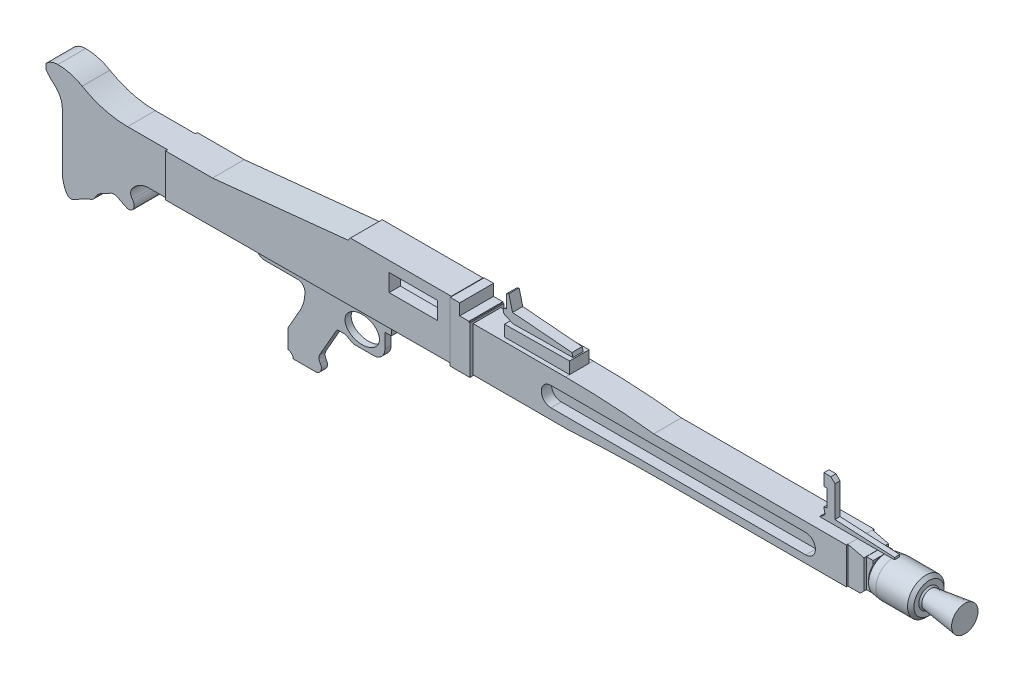
SolidWorks part; units mm, degrees
ref_plane "Front Plane" through (0, 0, 0) normal (0, 0, 1) x (1, 0, 0)
ref_plane "Top Plane" through (0, 0, 0) normal (0, 1, 0) x (1, 0, 0)
ref_plane "Right Plane" through (0, 0, 0) normal (1, 0, 0) x (0, 0, -1)
sketch "Sketch2" plane through (0, 0, 0) normal (0, 0, 1) x (1, 0, 0)
  line L0 (14.7008, 153.5347) -> (898.7815, 153.5347) construction
  dimension "D1" = 884.0807
sketch "Sketch3" plane through (0, 0, 0) normal (0, 0, 1) x (1, 0, 0)
  line L0 (133.1499, 139.8957) -> (133.1499, 98.4718)
  line L1 (133.1499, 98.4718) -> (411.7498, 99.671)
  line L2 (411.7498, 99.671) -> (411.7498, 156.4491)
  line L3 (411.7498, 156.4491) -> (313.434, 156.4491)
  line L4 (313.434, 156.4491) -> (311.325, 153.5347)
  line L5 (14.7008, 153.5347) -> (898.7815, 153.5347) construction
  line L6 (311.325, 153.5347) -> (179.0076, 139.8957)
  line L7 (179.0076, 139.8957) -> (133.1499, 139.8957)
extrude "Boss-Extrude1" add sketch "Sketch3" along normal mid plane 31
sketch "Sketch4" plane through (0, 0, 0) normal (0, 0, 1) x (1, 0, 0)
  line L0 (411.7498, 156.033) -> (420.9758, 156.033)
  line L1 (411.7498, 99.671) -> (411.7498, 156.4491) construction
  line L2 (420.9758, 156.033) -> (420.9758, 144.9785)
  line L3 (420.9758, 144.9785) -> (430.0091, 144.9785)
  line L4 (430.0091, 144.9785) -> (430.0091, 143.9886)
  line L5 (430.0091, 143.9886) -> (431.0197, 143.9886)
  line L6 (431.0197, 143.9886) -> (431.0197, 141.9943)
  line L7 (431.0197, 141.9943) -> (431.0197, 97.9537)
  line L8 (431.0197, 97.9537) -> (411.7498, 97.9537)
  line L9 (411.7498, 97.9537) -> (411.7498, 99.671)
  line L10 (411.7498, 99.671) -> (411.7498, 156.033)
extrude "Boss-Extrude2" add sketch "Sketch4" along normal mid plane 33
sketch "Sketch5" plane through (0, 0, 0) normal (0, 0, 1) x (1, 0, 0)
  line L0 (133.1499, 139.8957) -> (94.2529, 139.8957)
  line L1 (133.1499, 139.8957) -> (133.1499, 98.4718)
  line L2 (133.1499, 98.4718) -> (115.1309, 98.4718)
  line L3 (30.6087, 69.3461) -> (30.6087, 122.8292)
  line L4 (14.7008, 148.4374) -> (14.7008, 153.5347)
  arc A0 (94.2529, 139.8957) -> (49.9783, 151.9188) centre (94.2529, 227.4269) cw
  arc A1 (49.9783, 151.9188) -> (26.2526, 158.3616) centre (26.2526, 111.4559) ccw
  arc A2 (26.2526, 158.3616) -> (14.7008, 153.5347) centre (26.2526, 142.1251) ccw
  arc A3 (115.1309, 98.4718) -> (98.2336, 89.0087) centre (115.1309, 78.6544) ccw
  arc A4 (98.2336, 89.0087) -> (98.8895, 80.7837) centre (104.2099, 85.3466) ccw
  arc A5 (98.8895, 80.7837) -> (100.0051, 73.4816) centre (93.5886, 76.2376) cw
  arc A6 (100.0051, 73.4816) -> (93.5886, 70.9209) centre (95.5165, 75.4095) cw
  arc A7 (93.5886, 70.9209) -> (84.488, 75.4095) centre (131.7264, 159.714) cw
  arc A8 (84.488, 75.4095) -> (77.693, 75.4095) centre (81.0905, 69.3461) ccw
  arc A9 (77.693, 75.4095) -> (69.1582, 70.8723) centre (-29.0893, 265.9797) cw
  arc A10 (69.1582, 70.8723) -> (62.7211, 64.3963) centre (75.6482, 57.9841) ccw
  arc A11 (62.7211, 64.3963) -> (59.2285, 61.0407) centre (56.3051, 67.5788) cw
  arc A12 (59.2285, 61.0407) -> (41.7659, 52.0012) centre (129.4371, -95.9766) ccw
  arc A13 (41.7659, 52.0012) -> (34.8781, 53.7639) centre (39.2033, 56.3264) cw
  arc A14 (34.8781, 53.7639) -> (30.6087, 69.3461) centre (61.1788, 69.3461) cw
  arc A15 (30.6087, 122.8292) -> (22.4442, 139.8957) centre (8.6893, 122.8292) ccw
  arc A16 (22.4442, 139.8957) -> (14.7008, 148.4374) centre (45.7254, 168.7818) cw
extrude "Boss-Extrude3" add sketch "Sketch5" along normal mid plane 27
sketch "Sketch6" plane through (0, 0, 0) normal (0, 0, 1) x (1, 0, 0)
  line L0 (431.0197, 141.9851) -> (521.1439, 141.9851)
  line L1 (431.0197, 97.9537) -> (431.0197, 143.9886) construction
  line L2 (607.1546, 136.9962) -> (794.9048, 136.9962)
  line L3 (794.9048, 136.9962) -> (794.9048, 101.6278)
  line L4 (794.9048, 101.6278) -> (617.7858, 101.6278)
  line L5 (523.6562, 98.7043) -> (431.0197, 98.7043)
  line L6 (431.0197, 98.7043) -> (431.0197, 141.9851)
  arc A0 (521.1439, 141.9851) -> (607.1546, 136.9962) centre (521.1439, -601.9324) cw
  arc A1 (617.7858, 101.6278) -> (523.6562, 98.7043) centre (617.7858, -1415.198) ccw
extrude "Boss-Extrude4" add sketch "Sketch6" along normal mid plane 27
sketch "Sketch7" plane through (0, 0, 0) normal (0, 0, 1) x (1, 0, 0)
  line L0 (794.9048, 136.9962) -> (810.5012, 133.2202)
  line L1 (810.5012, 133.2202) -> (810.5012, 105.1026)
  line L2 (810.5012, 105.1026) -> (807.0264, 101.6278)
  line L3 (807.0264, 101.6278) -> (794.9048, 101.6278)
  line L4 (794.9048, 136.9962) -> (794.9048, 101.6278)
extrude "Boss-Extrude5" add sketch "Sketch7" along normal mid plane 24
sketch "Sketch8" plane through (0, 0, 0) normal (0, 0, 1) x (1, 0, 0)
  line L0 (810.5012, 132.9965) -> (816.9976, 132.9965)
  line L1 (810.5012, 105.1026) -> (810.5012, 133.2202) construction
  line L2 (816.9976, 132.9965) -> (816.9976, 105.1026)
  line L3 (816.9976, 105.1026) -> (810.5012, 105.1026)
  line L4 (810.5012, 105.1026) -> (810.5012, 132.9965)
extrude "Boss-Extrude6" add sketch "Sketch8" along normal mid plane 19
sketch "Sketch9" plane through (0, 0, 0) normal (0, 0, 1) x (1, 0, 0)
  line L0 (457.5847, 141.9851) -> (457.5847, 152.7766)
  line L1 (521.1439, 141.9851) -> (431.0197, 141.9851) construction
  line L2 (457.5847, 152.7766) -> (521.1439, 153.5347)
  line L3 (14.7008, 153.5347) -> (898.7815, 153.5347) construction
  line L4 (521.1439, 153.5347) -> (521.1439, 141.9851)
  line L5 (521.1439, 141.9851) -> (457.5847, 141.9851)
extrude "Boss-Extrude7" add sketch "Sketch9" along normal mid plane 19
sketch "Sketch10" plane through (0, 0, 0) normal (0, 0, 1) x (1, 0, 0)
  line L0 (519.8698, 153.5347) -> (518.9166, 157.2999)
  line L1 (14.7008, 153.5347) -> (898.7815, 153.5347) construction
  line L2 (518.9166, 157.2999) -> (460.9658, 162.1609)
  line L3 (460.9658, 162.1609) -> (457.4142, 176.1911)
  line L4 (457.4142, 176.1911) -> (455.0466, 174.9369)
  line L5 (455.0466, 174.9369) -> (455.0466, 162.1609)
  line L6 (455.0466, 155.9393) -> (460.9658, 152.8169)
  line L7 (521.1439, 153.5347) -> (457.5847, 152.7766) construction
  line L8 (460.9658, 152.8169) -> (519.8698, 153.5347)
  arc A0 (455.0466, 162.1609) -> (451.9358, 159.0501) centre (455.0466, 159.0501) ccw
  arc A1 (451.9358, 159.0501) -> (455.0466, 155.9393) centre (455.0466, 159.0501) ccw
extrude "Boss-Extrude8" add sketch "Sketch10" along normal mid plane 10 separate body
sketch "Sketch11" plane through (0, 0, 0) normal (0, 0, 1) x (1, 0, 0)
  line L0 (757.7007, 136.9962) -> (763.235, 141.021)
  line L1 (794.9048, 136.9962) -> (607.1546, 136.9962) construction
  line L2 (763.235, 141.021) -> (761.9898, 147.247)
  line L3 (761.9898, 147.247) -> (765.2092, 147.8909)
  line L4 (765.2092, 147.8909) -> (765.2092, 164.68)
  line L5 (765.2092, 164.68) -> (761.9898, 164.68)
  line L6 (761.9898, 164.68) -> (761.9898, 176.1636)
  line L7 (761.9898, 176.1636) -> (768.7693, 176.1636)
  line L8 (768.7693, 176.1636) -> (772.7816, 172.1512)
  line L9 (772.7816, 172.1512) -> (772.7816, 141.9895)
  line L10 (772.7816, 141.9895) -> (830.8844, 139.0086)
  line L11 (830.8844, 139.0086) -> (830.8844, 136.9962)
  line L12 (830.8844, 136.9962) -> (757.7007, 136.9962)
extrude "Boss-Extrude9" add sketch "Sketch11" along normal mid plane 5
sketch "Sketch12" plane through (0, 0, 0) normal (0, 0, 1) x (1, 0, 0)
  line L0 (208.8422, 98.7976) -> (208.8422, 92.0083)
  line L1 (133.1499, 98.4718) -> (411.7498, 99.671) construction
  line L2 (217.4889, 83.3616) -> (249.4184, 83.3616)
  line L3 (251.8692, 58.3778) -> (240.0102, 37.6418)
  line L4 (240.0102, 37.6418) -> (240.0102, 19.2458)
  line L5 (245.1891, 14.0669) -> (266.8401, 14.0669)
  line L6 (271.0539, 30.6103) -> (287.2395, 58.9114)
  line L7 (289.4063, 60.1684) -> (295.9274, 60.1684)
  line L8 (295.9274, 60.1684) -> (303.9879, 55.9915)
  line L9 (303.9879, 55.9915) -> (323.5844, 55.9915)
  line L10 (334.5626, 66.9698) -> (334.5626, 81.2581)
  line L11 (334.5626, 81.2581) -> (340.8552, 81.2581)
  line L12 (340.8552, 81.2581) -> (340.8552, 99.3658)
  line L13 (340.8552, 99.3658) -> (208.8422, 98.7976)
  arc A0 (208.8422, 92.0083) -> (217.4889, 83.3616) centre (217.4889, 92.0083) ccw
  arc A1 (249.4184, 83.3616) -> (256.6002, 76.1798) centre (249.4184, 76.1798) cw
  arc A2 (256.6002, 76.1798) -> (251.8692, 58.3778) centre (220.7417, 76.1798) cw
  arc A3 (240.0102, 19.2458) -> (245.1891, 14.0669) centre (240.0102, 14.0669) cw
  arc A4 (266.8401, 14.0669) -> (271.6285, 23.2042) centre (266.8401, 19.8902) ccw
  arc A5 (271.6285, 23.2042) -> (271.0539, 30.6103) centre (277.6908, 27.3999) cw
  arc A6 (287.2395, 58.9114) -> (289.4063, 60.1684) centre (289.4063, 57.6722) cw
  arc A7 (323.5844, 55.9915) -> (334.5626, 66.9698) centre (323.5844, 66.9698) ccw
  ellipse E0 centre (312.4473, 72.4103) end of major axis (329.2097, 72.4103) minor radius 12.7891
extrude "Boss-Extrude10" add sketch "Sketch12" along normal mid plane 6
sketch "Sketch13" plane through (0, 0, 0) normal (0, 0, 1) x (1, 0, 0)
  line L0 (816.9976, 119.0496) -> (904.5437, 119.0496) construction
  line L1 (816.9976, 105.1026) -> (816.9976, 132.9965) construction
  line L11 (816.9976, 119.0496) -> (816.9976, 132.9965)
  line L14 (816.9976, 132.9965) -> (819.7407, 135.7396)
  line L15 (819.7407, 135.7396) -> (827.9977, 136.934)
  line L16 (827.9977, 136.934) -> (858.9276, 136.934)
  line L17 (858.9276, 136.934) -> (862.0293, 133.8506)
  line L18 (862.0293, 133.8506) -> (862.0293, 128.988)
  line L19 (862.0293, 128.988) -> (863.44, 127.5856)
  line L20 (863.44, 127.5856) -> (896.8883, 131.9309)
  line L21 (896.8883, 131.9309) -> (896.8883, 119.0496)
  line L22 (896.8883, 119.0496) -> (816.9976, 119.0496)
revolve "Revolve21" add sketch "Sketch13" angle 360 about L0
sketch "Sketch14" plane through (0, 0, 13.5) normal (0, 0, 1) x (1, 0, 0)
  line L0 (506.974, 118.3493) -> (755.2891, 118.3493) construction
  line L1 (506.974, 127.827) -> (755.2891, 127.827)
  line L2 (506.974, 108.8716) -> (755.2891, 108.8716)
  arc A0 (506.974, 127.827) -> (506.974, 108.8716) centre (506.974, 118.3493) ccw
  arc A1 (755.2891, 108.8716) -> (755.2891, 127.827) centre (755.2891, 118.3493) ccw
  point P2 (631.1315, 118.3493)
extrude "Cut-Extrude1" cut sketch "Sketch14" against normal blind 10
sketch "Sketch15" plane through (0, 0, -13.5) normal (0, 0, -1) x (-1, 0, 0)
  line L0 (-794.9048, 136.9962) -> (-607.1546, 136.9962) construction
  line L1 (-772.5156, 124.9962) -> (-733.5156, 124.9962)
  line L2 (-772.5156, 124.9962) -> (-772.5156, 112.6016)
  line L3 (-772.5156, 112.6016) -> (-733.5156, 112.6016)
  line L4 (-733.5156, 124.9962) -> (-733.5156, 112.6016)
  dimension "D1" = 39
  dimension "D2" = 12.3945
  dimension "D3" = 12
extrude "Cut-Extrude2" cut sketch "Sketch15" against normal blind 10
pattern_linear "LPattern1" count 5 spacing 65 along (-1, 0, 0) of "Cut-Extrude2"
sketch "Sketch16" plane through (0, 0, -15.5) normal (0, 0, -1) x (-1, 0, 0)
  line L0 (-398.6154, 156.4491) -> (-398.6154, 139.4491) construction
  line L1 (-411.7498, 156.4491) -> (-313.434, 156.4491) construction
  line L3 (-398.6154, 139.4491) -> (-311.6154, 139.4491)
  line L4 (-398.6154, 139.4491) -> (-398.6154, 126.4491)
  line L5 (-398.6154, 126.4491) -> (-311.6154, 126.4491)
  line L6 (-311.6154, 139.4491) -> (-311.6154, 126.4491)
  dimension "D1" = 17
  dimension "D2" = 87
  dimension "D3" = 13
extrude "Cut-Extrude3" cut sketch "Sketch16" against normal blind 20
sketch "Sketch17" plane through (0, 0, 15.5) normal (0, 0, 1) x (1, 0, 0)
  line L1 (351.1334, 146.2542) -> (398.1334, 146.2542)
  line L2 (351.1334, 146.2542) -> (351.1334, 129.2542)
  line L3 (351.1334, 129.2542) -> (398.1334, 129.2542)
  line L4 (398.1334, 146.2542) -> (398.1334, 129.2542)
  dimension "D1" = 47
  dimension "D2" = 17
extrude "Cut-Extrude4" cut sketch "Sketch17" against normal blind 20
